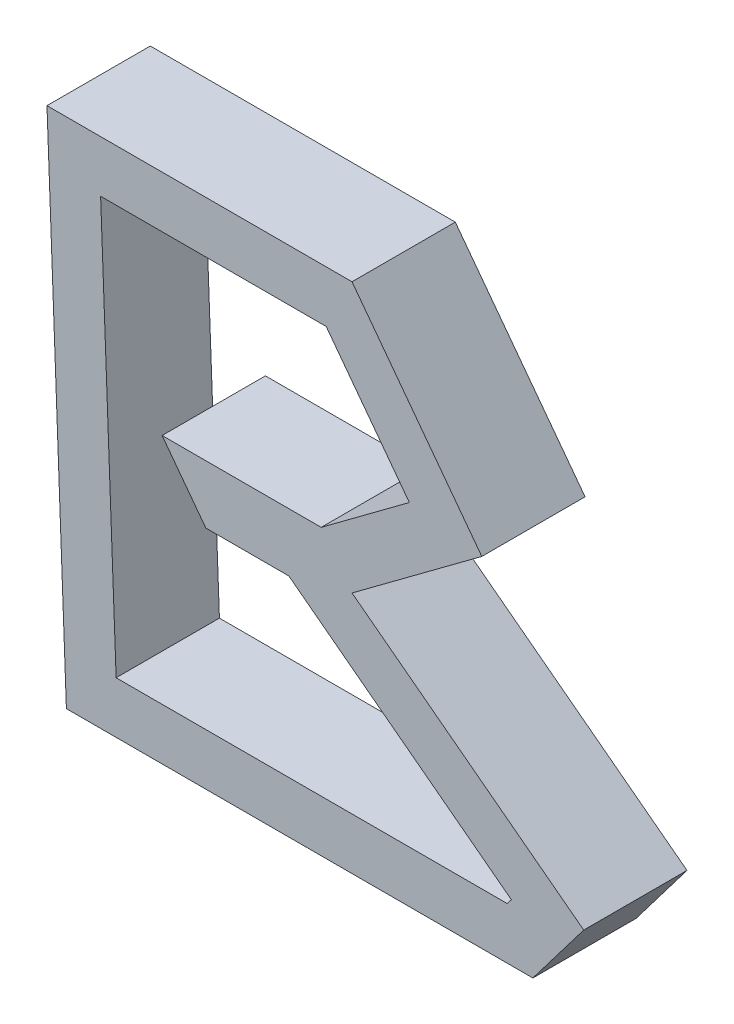
SolidWorks part; units mm, degrees
ref_plane "Front Plane" through (0, 0, 0) normal (0, 0, 1) x (1, 0, 0)
ref_plane "Top Plane" through (0, 0, 0) normal (0, 1, 0) x (1, 0, 0)
ref_plane "Right Plane" through (0, 0, 0) normal (1, 0, 0) x (0, 0, -1)
sketch "Sketch1" plane through (0, 0, 0) normal (0, 0, 1) x (1, 0, 0)
  line L17 (-32.5758, -52.904) -> (-36.3349, 46.3384)
  line L18 (-36.3349, 46.3384) -> (22.7273, 46.3384)
  line L19 (22.7273, 46.3384) -> (47.8539, 12.8363)
  line L20 (47.8539, 12.8363) -> (22.7273, -5.8505)
  line L21 (22.7273, -5.8505) -> (67.5928, -39.9414)
  line L22 (67.5928, -39.9414) -> (57.7432, -52.904)
  line L23 (57.7432, -52.904) -> (-32.5758, -52.904)
  line L24 (-18.1332, -37.904) -> (-20.756, 31.3384)
  line L25 (-20.756, 31.3384) -> (15.2273, 31.3384)
  line L26 (15.2273, 31.3384) -> (26.2626, 17.0455)
  line L28 (9.0909, -8.4596) -> (40.1184, -37.904)
  line L30 (40.1184, -37.904) -> (-18.1332, -37.904)
  line L31 (9.0909, -8.4596) -> (-2.5253, -8.4596)
  line L32 (-2.5253, -8.4596) -> (-12.1212, 1.1364)
  line L33 (-12.1212, 1.1364) -> (10.3535, 1.1364)
  line L34 (10.3535, 1.1364) -> (26.2626, 17.0455)
extrude "Boss-Extrude4" add sketch "Sketch1" along normal blind 20 contours L18 L19 L20 L21 L22 L23 L17
sketch "Sketch3" plane through (0, 0, 20) normal (0, 0, 1) x (1, 0, 0)
  line L14 (10.4941, -9.1145) -> (-5.5757, -9.1145)
  line L15 (-5.5757, -9.1145) -> (-14.0418, 2.1737)
  line L16 (-14.0418, 2.1737) -> (16.7597, 2.1737)
  line L18 (-22.9474, -42.904) -> (-25.949, 36.3384)
  line L19 (-25.949, 36.3384) -> (17.7273, 36.3384)
  line L20 (17.7273, 36.3384) -> (33.8296, 14.8687)
  line L21 (33.8296, 14.8687) -> (16.7597, 2.1737)
  line L27 (16.6772, -13.8127) -> (53.5805, -41.8535)
  line L28 (53.5805, -41.8535) -> (52.7823, -42.904)
  line L29 (52.7823, -42.904) -> (-32.5758, -42.904)
  line L30 (10.4941, -9.1145) -> (53.5805, -41.8535)
  line L31 (53.5805, -41.8535) -> (52.7823, -42.904)
  line L32 (52.7823, -42.904) -> (-22.9474, -42.904)
  dimension "D2" = 10
extrude "Cut-Extrude1" cut sketch "Sketch3" against normal through all
